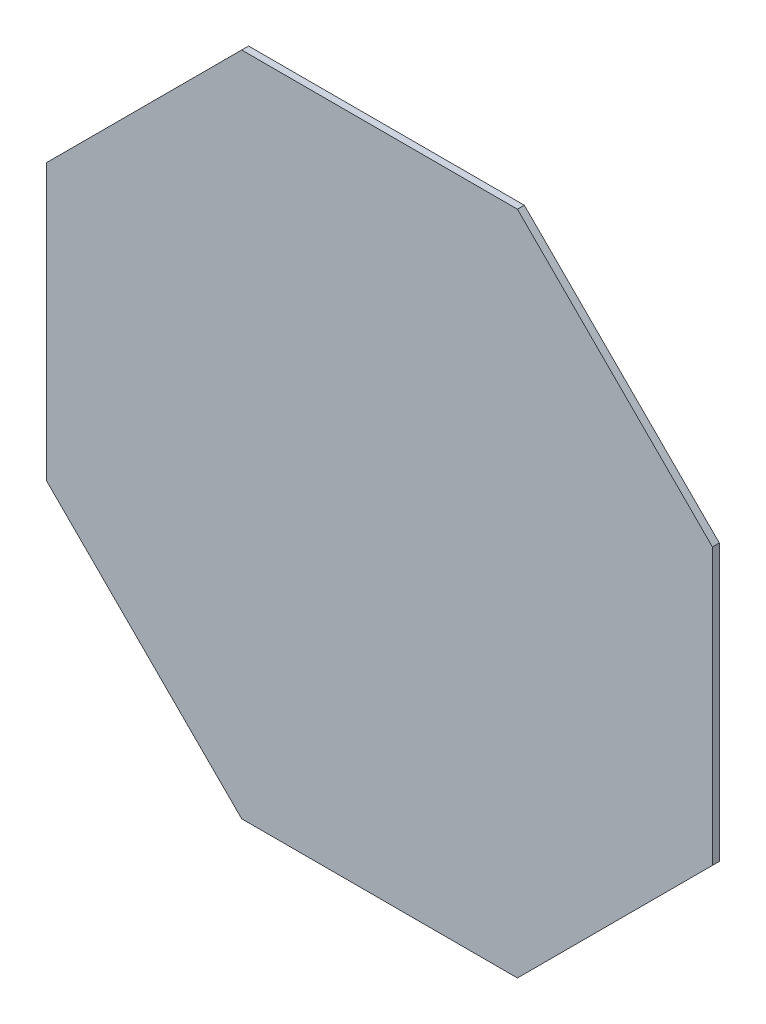
SolidWorks part; units mm, degrees
material "1023 Carbon Steel Sheet (SS)"
ref_plane "Front Plane" through (0, 0, 0) normal (1, 0, 0) x (0, 1, 0)
ref_plane "Top Plane" through (0, 0, 0) normal (0, 0, 1) x (0, 1, 0)
ref_plane "Right Plane" through (0, 0, 0) normal (0, 1, 0) x (-1, 0, 0)
sketch "Sketch1" plane through (0, 0, 0) normal (0, 0, 1) x (0, 1, 0)
  line L1 (-60, 144.8528) -> (-144.8528, 60)
  line L2 (-144.8528, 60) -> (-144.8528, -60)
  line L3 (-144.8528, -60) -> (-60, -144.8528)
  line L4 (-60, -144.8528) -> (60, -144.8528)
  line L5 (60, -144.8528) -> (144.8528, -60)
  line L6 (144.8528, -60) -> (144.8528, 60)
  line L7 (144.8528, 60) -> (60, 144.8528)
  line L8 (60, 144.8528) -> (-60, 144.8528)
  circle A0 centre (0, 0) radius 144.8528 construction
  point P1 (0, 144.8528)
  dimension "D1" = 120
extrude "Boss-Extrude1" add sketch "Sketch1" along normal blind 3
